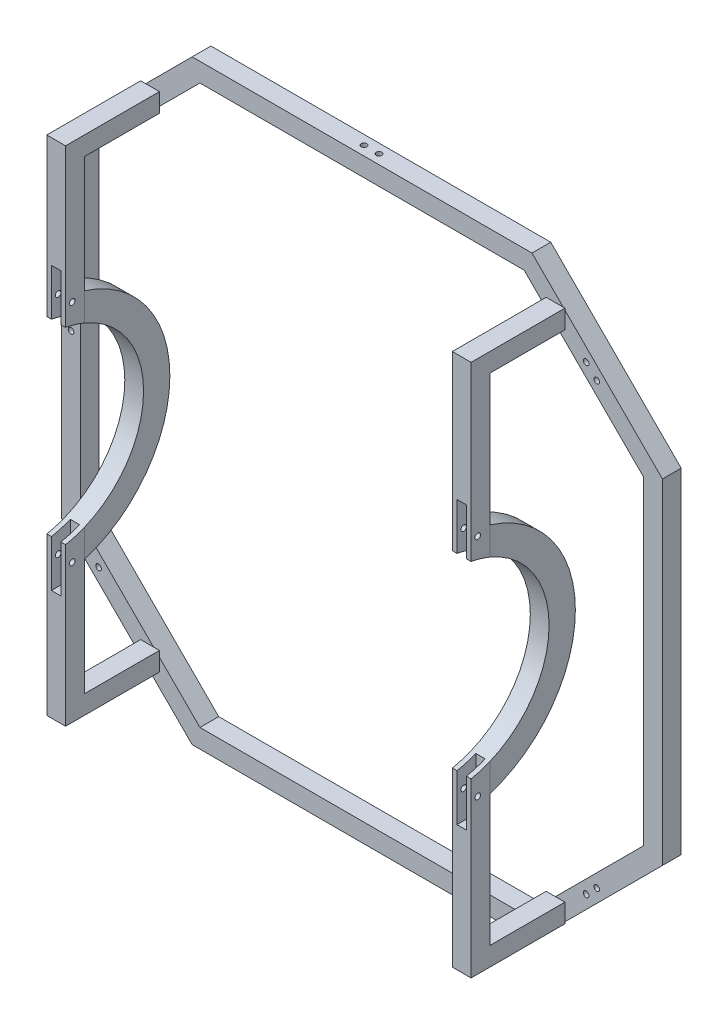
SolidWorks part; units mm, degrees
material "6063-O"
ref_plane "Ön Düzlem" through (0, 0, 0) normal (0, 0, 1) x (1, 0, 0)
ref_plane "Üst Düzlem" through (0, 0, 0) normal (0, 1, 0) x (1, 0, 0)
ref_plane "Sağ Düzlem" through (0, 0, 0) normal (1, 0, 0) x (0, 0, -1)
sketch "Çizim1" plane through (0, 0, 0) normal (0, 0, 1) x (1, 0, 0)
  line L0 (-150, 85) -> (-150, -85)
  line L1 (-150, -85) -> (-86.3604, -148.6396)
  line L3 (-150, 85) -> (-86.3604, 148.6396)
  line L6 (-160, 89.1421) -> (-90.5025, 158.6396)
  line L10 (-160, -89.1421) -> (-90.5025, -158.6396)
  line L11 (-160, 89.1421) -> (-160, -89.1421)
  line L12 (136.5685, 0) -> (-160, 0) construction
  line L13 (0, 0) -> (0, 45.7786) construction
  line L14 (133.6396, 148.6396) -> (133.6396, -148.6396) construction
  line L15 (-90.5025, 158.6396) -> (143.6396, 158.6396) construction
  line L16 (-86.3604, 148.6396) -> (133.6396, 148.6396) construction
  line L17 (143.6396, 158.6396) -> (143.6396, -158.6396) construction
  line L18 (-86.3604, -148.6396) -> (133.6396, -148.6396) construction
  line L19 (-90.5025, -158.6396) -> (143.6396, -158.6396) construction
  line L20 (-90.5025, 158.6396) -> (90.5025, 158.6396)
  line L21 (-90.5025, -158.6396) -> (90.5025, -158.6396)
  line L22 (86.3604, 148.6396) -> (-86.3604, 148.6396)
  line L23 (160, 89.1421) -> (160, -89.1421)
  line L24 (86.3604, -148.6396) -> (-86.3604, -148.6396)
  line L25 (160, -89.1421) -> (90.5025, -158.6396)
  line L26 (160, 89.1421) -> (90.5025, 158.6396)
  line L27 (150, 85) -> (86.3604, 148.6396)
  line L28 (150, -85) -> (86.3604, -148.6396)
  line L29 (150, 85) -> (150, -85)
  point P17 (-160, 0)
  point P27 (0, 158.6396)
  point P28 (0, -148.6396)
  point P29 (0, 148.6396)
  point P30 (0, -158.6396)
  dimension "D1" = 45
  dimension "D2" = 45
  dimension "D3" = 170
  dimension "D4" = 90
  dimension "D7" = 160
  dimension "D8" = 63.6396
  dimension "D6" = 10
extrude "Yükseklik-Ekstrüzyon2" add sketch "Çizim1" along normal blind 10
ref_plane "Düzlem1" through (0, -123.89, 0) normal (0, 1, 0) x (1, 0, 0)
sketch "Çizim3" plane through (0, -123.89, 0) normal (0, 1, 0) x (1, 0, 0)
  line L0 (-117.927, -10) -> (-117.927, -50)
  line L2 (-160, -10) -> (-90.5025, -10) construction
  line L3 (-107.927, -10) -> (-107.927, -50)
  line L4 (-117.927, -50) -> (-107.927, -50)
  line L5 (-117.927, -10) -> (-117.927, -50) construction
  line L6 (-117.927, -10) -> (-107.927, -10)
  dimension "D2" = 40
  dimension "D1" = 10
extrude "Yükseklik-Ekstrüzyon3" add sketch "Çizim3" against normal blind 10
ref_plane "Düzlem2" through (0, 0, 50) normal (0, 0, 1) x (1, 0, 0)
sketch "Çizim4" plane through (0, 0, 50) normal (0, 0, 1) x (1, 0, 0)
  line L0 (27.5, -123.89) -> (-27.5, -123.89) construction
  line L2 (-107.927, 0) -> (-107.927, -133.89)
  line L4 (-117.927, 0) -> (-117.927, -133.89)
  line L5 (-117.927, -133.89) -> (-117.927, -123.89)
  line L6 (-107.927, -123.89) -> (-107.927, -133.89)
  line L7 (-117.927, -133.89) -> (-117.927, -123.89) construction
  line L8 (-107.927, 0) -> (-117.927, 0)
  line L9 (-117.927, -133.89) -> (-117.927, -123.89) construction
  line L11 (-117.927, -133.89) -> (-107.927, -133.89) construction
  line L14 (-117.927, -133.89) -> (-107.927, -133.89)
  point P0 (-19.5864, 0)
  dimension "D1" = 10
extrude "Yükseklik-Ekstrüzyon4" add sketch "Çizim4" along normal blind 10 contours L4 L14 L2 L8
ref_plane "Düzlem3" through (0, -142, 0) normal (0, 1, 0) x (1, 0, 0)
sketch "Çizim6" plane through (0, -142, 0) normal (0, 1, 0) x (1, 0, 0)
  line L13 (98.073, -10) -> (98.073, -60)
  line L14 (90.5025, -10) -> (160, -10) construction
  line L15 (98.073, -60) -> (108.073, -60)
  line L16 (108.073, -60) -> (108.073, -10)
  line L17 (108.073, -10) -> (98.073, -10)
  line L18 (-117.927, -10) -> (-117.927, -60) construction
  dimension "D1" = 226
  dimension "D2" = 10
  dimension "D3" = 50
extrude "Yükseklik-Ekstrüzyon5" add sketch "Çizim6" along normal blind 10
sketch "Çizim7" plane through (0, 0, 50) normal (0, 0, 1) x (1, 0, 0)
  line L0 (108.073, -142) -> (108.073, 0)
  line L1 (108.073, 0) -> (98.073, 0)
  line L2 (108.073, -142) -> (98.073, -142)
  line L3 (98.073, -142) -> (98.073, 0)
extrude "Yükseklik-Ekstrüzyon6" add sketch "Çizim7" along normal blind 10
mirror "Aynalama1" about plane through (0, 0, 0) normal (0, 1, 0) of "Yükseklik-Ekstrüzyon4", "Yükseklik-Ekstrüzyon5", "Yükseklik-Ekstrüzyon3", "Yükseklik-Ekstrüzyon6"
sketch "Çizim8" plane through (0, 0, 10) normal (0, 0, 1) x (1, 0, 0)
  line L0 (-150, 0) -> (-160, 0) construction
  line L1 (-160, -89.1421) -> (-117.927, -131.2152) construction
  line L2 (-150, 85) -> (-150, -85) construction
  line L3 (-160, 89.1421) -> (-160, -89.1421) construction
  line L5 (160, 89.1421) -> (108.073, 141.0691) construction
  line L8 (86.3604, -148.6396) -> (98.073, -136.927) construction
  line L9 (-117.927, 131.2152) -> (-160, 89.1421) construction
  circle A4 centre (125, 117.0711) radius 1.5
  circle A5 centre (119.3431, 122.7279) radius 1.5
  circle A6 centre (119.3431, -122.7279) radius 1.5
  circle A7 centre (125, -117.0711) radius 1.5
  circle A12 centre (-140.3431, 101.7279) radius 1.5
  circle A13 centre (-146, 96.0711) radius 1.5
  circle A14 centre (-140.3431, -101.7279) radius 1.5
  circle A15 centre (-146, -96.0711) radius 1.5
  circle A16 centre (-155, 0) radius 1.5
  dimension "D4" = 3
  dimension "D5" = 4
  dimension "D7" = 5
  dimension "D11" = 3
  dimension "D14" = 8
  dimension "D15" = 3
  dimension "D19" = 25
  dimension "D27" = 3
  dimension "D28" = 3
  dimension "D22" = 3
  dimension "D3" = 8
  dimension "D6" = 5
  dimension "D8" = 5
  dimension "D9" = 4
  dimension "D10" = 8
  dimension "D12" = 5
  dimension "D13" = 5
  dimension "D16" = 25
  dimension "D17" = 5
  dimension "D18" = 5
  dimension "D20" = 5
  dimension "D21" = 85
  dimension "D26" = 8
extrude "Kes-Ekstrüzyon1" cut sketch "Çizim8" against normal blind 35
sketch "Çizim9" plane through (0, -142, 0) normal (0, 1, 0) x (1, 0, 0)
  circle A0 centre (-4, -4.9928) radius 1.5
  circle A1 centre (4, -4.9928) radius 1.5
  dimension "D2" = 3
  dimension "D1" = 4
  dimension "D3" = 8
extrude "Kes-Ekstrüzyon2" cut sketch "Çizim9" along normal blind 374
ref_plane "Düzlem4" through (-112.93, 0, 0) normal (1, 0, 0) x (0, 0, -1)
sketch "Çizim12" plane through (-112.93, 0, 0) normal (1, 0, 0) x (0, 0, -1)
  circle A0 centre (-69.4435, 0) radius 51
  point P0 (-69.4435, 0)
  dimension "D1" = 102
ref_plane "Düzlem5" through (103.07, 0, 0) normal (1, 0, 0) x (0, 0, -1)
extrude "Kes-Ekstrüzyon4" cut sketch "Çizim12" against normal mid plane 676
sketch "Çizim19" plane through (-112.93, 0, 0) normal (1, 0, 0) x (0, 0, -1)
  line L4 (-50, -62.0238) -> (-50, -47.1482)
  line L5 (-50, 62.0238) -> (-50, 47.1482)
  arc A1 (-50, -62.0238) -> (-50, 62.0238) centre (-69.4435, 0) ccw
  arc A2 (-50, -47.1482) -> (-50, 47.1482) centre (-69.4435, 0) ccw
  dimension "D2" = 130
extrude "Yükseklik-Ekstrüzyon7" add sketch "Çizim19" along normal mid plane 10
sketch "Çizim20" plane through (103.07, 0, 0) normal (1, 0, 0) x (0, 0, -1)
  line L2 (-50, -47.1482) -> (-50, -62.0238)
  line L6 (-50, -47.1482) -> (-50, -62.0238)
  line L8 (-50, 62.0238) -> (-50, 47.1482)
  line L9 (-50, 62.0238) -> (-50, 47.1482)
  arc A2 (-50, -62.0238) -> (-50, 62.0238) centre (-69.4435, 0) ccw
  arc A3 (-50, -47.1482) -> (-50, 47.1482) centre (-69.4435, 0) ccw
  arc A4 (-50, -62.0238) -> (-50, 62.0238) centre (-69.4435, 0) ccw
  arc A5 (-50, -47.1482) -> (-50, 47.1482) centre (-69.4435, 0) ccw
  dimension "D1" = 0
extrude "Yükseklik-Ekstrüzyon8" add sketch "Çizim20" along normal mid plane 10
sketch "Çizim21" plane through (-112.93, 0, 0) normal (1, 0, 0) x (0, 0, -1)
  line L5 (-50, 174.57) -> (-50, -174.57) construction
  line L6 (-63.2751, 75) -> (-50, 75)
  line L7 (-63.2751, 75) -> (-63.2751, -75)
  line L8 (-63.2751, -75) -> (-50, -75)
  line L9 (-50, 75) -> (-50, -75)
  line L10 (-63.2751, 75) -> (-50, -75) construction
  line L11 (-63.2751, -75) -> (-50, 75) construction
  point P0 (-56.6376, 0)
  dimension "D1" = 150
extrude "Kes-Ekstrüzyon5" cut sketch "Çizim21" against normal mid plane 5
sketch "Çizim22" plane through (103.07, 0, 0) normal (1, 0, 0) x (0, 0, -1)
  line L5 (-50, -62.0238) -> (-50, -123.89) construction
  line L6 (-65.4707, 75) -> (-50, 75)
  line L7 (-65.4707, 75) -> (-65.4707, -75)
  line L8 (-65.4707, -75) -> (-50, -75)
  line L9 (-50, 75) -> (-50, -75)
  line L10 (-65.4707, 75) -> (-50, -75) construction
  line L11 (-65.4707, -75) -> (-50, 75) construction
  point P0 (-57.7354, 0)
  dimension "D1" = 150
extrude "Kes-Ekstrüzyon6" cut sketch "Çizim22" against normal mid plane 5
sketch "Çizim23" plane through (-112.93, 0, 0) normal (1, 0, 0) x (0, 0, -1)
  circle A0 centre (-56.4435, 60) radius 1.5
  arc A1 (-50, -47.1482) -> (-50, 47.1482) centre (-69.4435, 0) ccw construction
  circle A2 centre (-56.4435, -60) radius 1.5
  dimension "D1" = 13
  dimension "D2" = 3
  dimension "D3" = 3
  dimension "D4" = 120
  dimension "D5" = 60
extrude "Kes-Ekstrüzyon7" cut sketch "Çizim23" against normal mid plane 484
